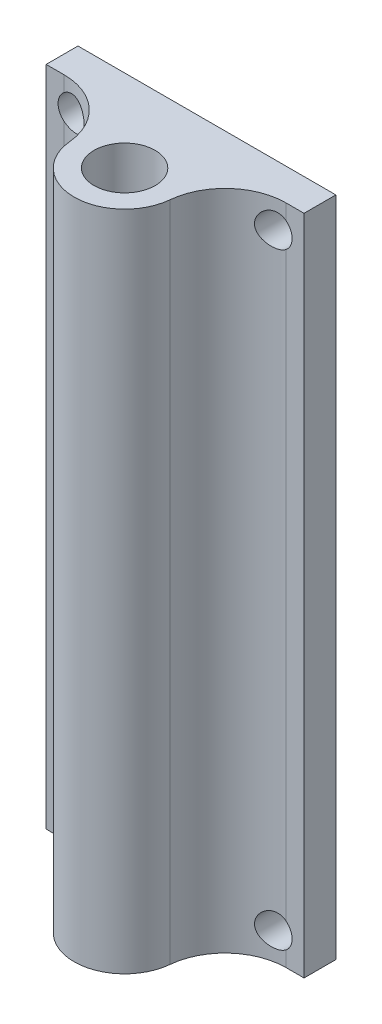
SolidWorks part; units mm, degrees
ref_plane "Front Plane" through (0, 0, 0) normal (0, 0, 1) x (1, 0, 0)
ref_plane "Top Plane" through (0, 0, 0) normal (0, 1, 0) x (1, 0, 0)
ref_plane "Right Plane" through (0, 0, 0) normal (1, 0, 0) x (0, 0, -1)
sketch "Sketch2" plane through (0, 0, 0) normal (0, 1, 0) x (1, 0, 0)
  line L0 (-16.2, 10.34) -> (16.2, 10.34)
  line L1 (-6.34, 6.34) -> (-16.2, 6.34)
  line L2 (-16.2, 6.34) -> (-16.2, 10.34)
  line L3 (6.34, 6.34) -> (16.2, 6.34)
  line L4 (16.2, 6.34) -> (16.2, 10.34)
  line L5 (0, 0) -> (0, 10486.5096) construction
  line L6 (-6.34, 6.34) -> (6.34, 6.34) construction
  line L7 (-6.34, 0) -> (-6.34, 6.34)
  line L8 (6.34, 0) -> (6.34, 6.34)
  circle A0 centre (0, 0) radius 6.34
  circle A3 centre (0, 0) radius 3.84
  dimension "D3" = 7.68
  dimension "D1" = 4
  dimension "D2" = 32.4
  dimension "D4" = 2.5
extrude "Boss-Extrude1" add sketch "Sketch2" along normal blind 83.2 contours A0 L8 L3 L4 L0 L2 L1 L7 | A0 A3
ref_plane "Plane1" through (0, 0, -20.34) normal (0, 0, -1) x (-1, 0, 0)
fillet "Fillet1" radius 7.68 2 edges at (-6.34, 41.6, -6.34) (6.34, 41.6, -6.34)
sketch "Sketch3" plane through (0, 0, -20.34) normal (0, 0, -1) x (-1, 0, 0)
  line L0 (0, 57.6421) -> (0, -49942.3579) construction
  line L1 (16.2, 83.2) -> (-16.2, 83.2) construction
  line L2 (-9.7711, 41.6) -> (49990.2289, 41.6) construction
  line L3 (-16.2, 83.2) -> (-16.2, 0) construction
  line L4 (16.2, 83.2) -> (16.2, 0) construction
  circle A0 centre (-12.7, 79.7) radius 2
  circle A1 centre (12.7, 79.7) radius 2
  circle A2 centre (-12.7, 3.5) radius 2
  circle A3 centre (12.7, 3.5) radius 2
  point P12 (0, 83.2)
  point P18 (-16.2, 41.6)
  point P21 (16.2, 41.6)
  dimension "D1" = 4
  dimension "D2" = 76.2
  dimension "D3" = 25.4
extrude "Cut-Extrude1" cut sketch "Sketch3" against normal through all both and the other way through all contours A1 | A3 | A2 | A0
equation "\"flightcomputer_type\" = 1'Type of computer."
equation "\"0_telemetrum_w\"= .750in"
equation "\"0_telemetrum_l\"= 2.250in"
equation "\"1_telemega_w\"= 1in"
equation "\"1_telemega_l\"= 3in"
equation "\"fc_width\"= IIF ( \"flightcomputer_type\" = 0 , \"0_telemetrum_w\" , 0 ) + IIF ( \"flightcomputer_type\" = 1 , \"1_telemega_w\" , 0 )"
equation "\"fc_length\"= IIF ( \"flightcomputer_type\" = 0 , \"0_telemetrum_l\" , 0 ) + IIF ( \"flightcomputer_type\" = 1 , \"1_telemega_l\" , 0 )"
equation "\"edge_offset\" = 7mm"
equation "\"m3_heatset_diameter\"= 4.16mm"
equation "\"m3_heatset_diameter_offset\"= .16mm"
equation "\"m3_hs_df\"= \"m3_heatset_diameter\" - \"m3_heatset_diameter_offset\""
equation "\"D2@Sketch2\"=\"fc_width\"+\"edge_offset\""
equation "\"threaded_rod_OD\"= 7.68mm"
equation "\"rod_wall_thickness\"= .25cm"
equation "\"D3@Sketch2\"=\"threaded_rod_OD\""
equation "\"D4@Sketch2\"=\"rod_wall_thickness\""
equation "\"D1@Boss-Extrude1\"=\"fc_length\"+\"edge_offset\""
equation "\"D1@Sketch3\"=\"m3_hs_df\""
equation "\"D2@Sketch3\"=\"fc_length\""
equation "\"D3@Sketch3\"=\"fc_width\""
equation "\"D1@Fillet1\"=\"threaded_rod_OD\""
